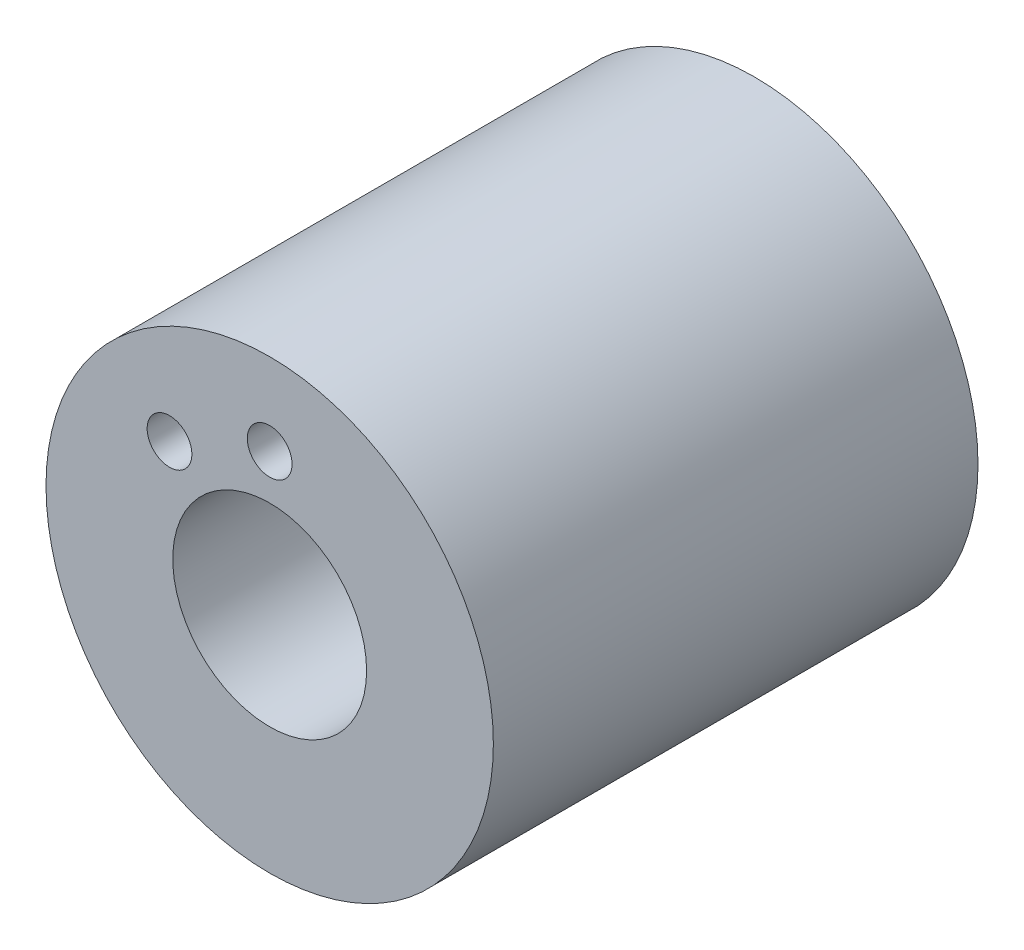
SolidWorks part; units mm, degrees
material "Plain Carbon Steel"
ref_plane "Front Plane" through (0, 0, 0) normal (0, 0, 1) x (1, 0, 0)
ref_plane "Top Plane" through (0, 0, 0) normal (0, 1, 0) x (1, 0, 0)
ref_plane "Right Plane" through (0, 0, 0) normal (1, 0, 0) x (0, 0, -1)
sketch "Sketch1" plane through (0, 0, 0) normal (0, 0, 1) x (1, 0, 0)
  line L0 (0, 0) -> (0, 50000) construction
  line L1 (-0.5228, 0.5228) -> (-35177.2244, 35177.2244) construction
  circle A0 centre (0, 0) radius 15
  circle A1 centre (0, 0) radius 6.5
  circle A2 centre (0, 0) radius 9.5 construction
  circle A3 centre (0, 9.5) radius 1.5
  circle A4 centre (-6.7175, 6.7175) radius 1.5
  point P14 (-2.9677, 9.0246)
  dimension "D1" = 30
  dimension "D2" = 19
  dimension "D3" = 13
  dimension "D4" = 3
  dimension "D5" = 45
extrude "Boss-Extrude1" add sketch "Sketch1" along normal mid plane 32.5
